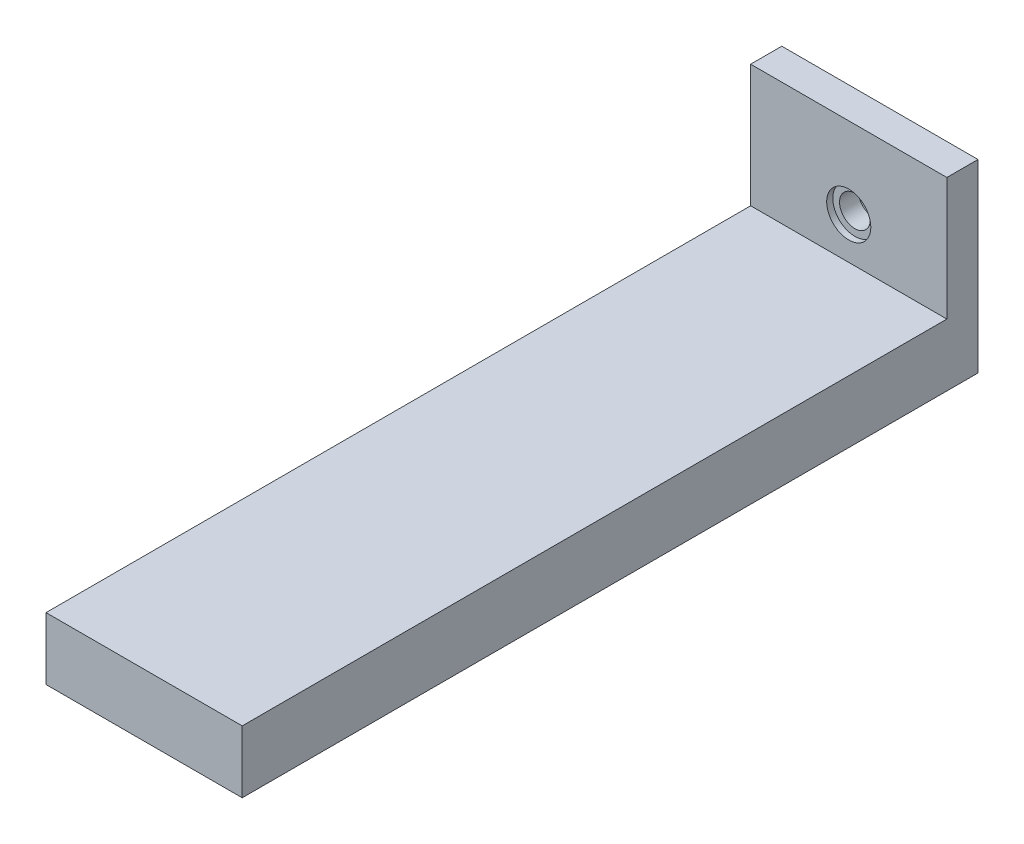
SolidWorks part; units mm, degrees
ref_plane "Alzado" through (0, 0, 0) normal (0, 0, 1) x (1, 0, 0)
ref_plane "Planta" through (0, 0, 0) normal (0, 1, 0) x (1, 0, 0)
ref_plane "Vista lateral" through (0, 0, 0) normal (1, 0, 0) x (0, 0, -1)
sketch "Croquis1" plane through (0, 0, 0) normal (0, 0, 1) x (1, 0, 0)
  line L1 (80, -25.4) -> (-80, -25.4)
  line L2 (80, -25.4) -> (80, 25.4)
  line L3 (80, 25.4) -> (-80, 25.4)
  line L4 (-80, -25.4) -> (-80, 25.4)
  line L5 (80, -25.4) -> (-80, 25.4) construction
  line L6 (80, 25.4) -> (-80, -25.4) construction
  point P0 (0, 0)
  dimension "D1" = 160
  dimension "D2" = 50.8
extrude "Saliente-Extruir1" add sketch "Croquis1" along normal mid plane 600
sketch "Croquis2" plane through (0, 25.4, 0) normal (0, 1, 0) x (1, 0, 0)
  line L0 (80, -300) -> (80, 300) construction
  line L1 (-80, 300) -> (80, 300)
  line L2 (-80, 300) -> (-80, 274.6)
  line L3 (-80, 274.6) -> (80, 274.6)
  line L4 (80, 300) -> (80, 274.6)
  dimension "D1" = 25.4
extrude "Saliente-Extruir2" add sketch "Croquis2" along normal blind 100
sketch "Croquis3" plane through (0, 0, -274.6) normal (0, 0, 1) x (1, 0, 0)
  line L2 (0, 71.2349) -> (0, 59.2349) construction
  circle A0 centre (0, 59.2349) radius 12.5
  dimension "D1" = 25
extrude "Cortar-Extruir1" cut sketch "Croquis3" against normal blind 100
sketch "Croquis4" plane through (0, 0, -274.6) normal (0, 0, 1) x (1, 0, 0)
  circle A0 centre (0, 59.2349) radius 18
  dimension "D1" = 36
extrude "Cortar-Extruir2" cut sketch "Croquis4" against normal blind 5
sketch "Croquis5" plane through (0, 0, -300) normal (0, 0, -1) x (-1, 0, 0)
  circle A0 centre (0, 59.2349) radius 18
  dimension "D1" = 36
extrude "Cortar-Extruir3" cut sketch "Croquis5" against normal blind 5
